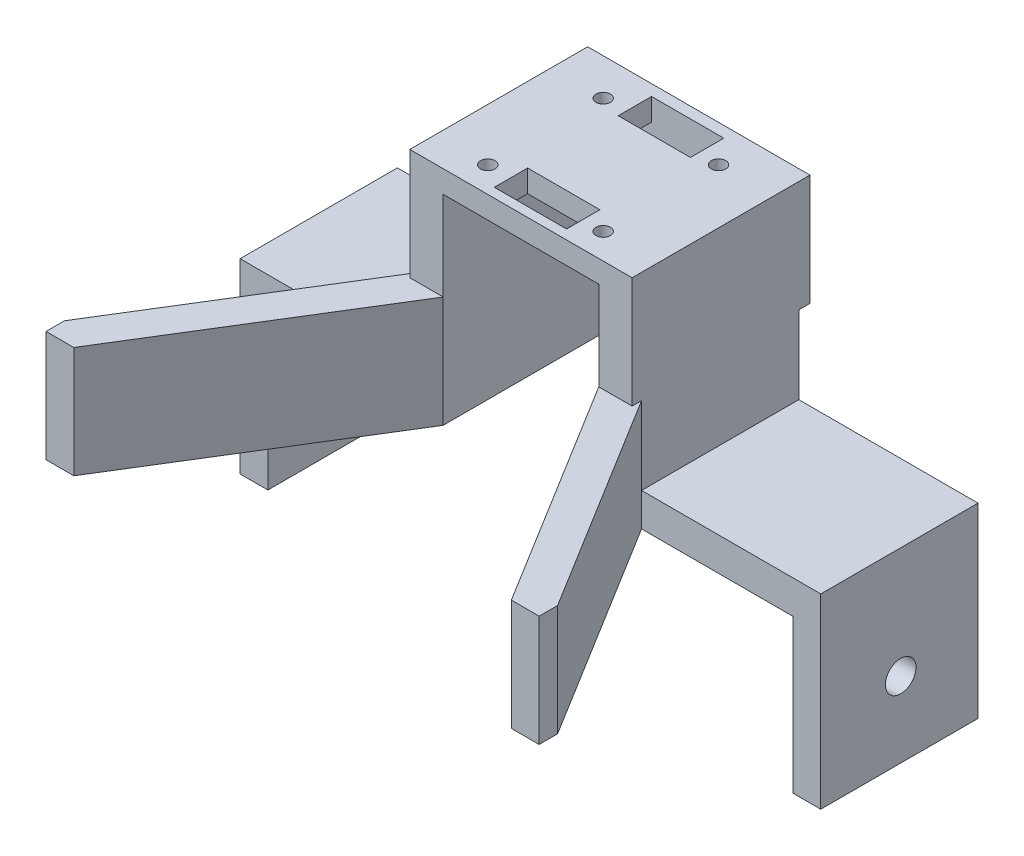
SolidWorks part; units mm, degrees
ref_plane "Front Plane" through (0, 0, 0) normal (0, 0, 1) x (1, 0, 0)
ref_plane "Top Plane" through (0, 0, 0) normal (0, 1, 0) x (1, 0, 0)
ref_plane "Right Plane" through (0, 0, 0) normal (1, 0, 0) x (0, 0, -1)
sketch "Sketch1" plane through (0, 0, 0) normal (0, 1, 0) x (1, 0, 0)
  line L0 (6.35, 4.2199) -> (-24.6, 54.3595)
  line L2 (6.35, 0) -> (6.35, 4.2199)
  line L5 (0, 0) -> (-32.22, 52.1971)
  line L6 (-32.22, 52.1971) -> (-32.22, 90.2971)
  line L7 (-32.22, 90.2971) -> (-24.6, 90.2971)
  line L8 (-24.6, 90.2971) -> (-24.6, 54.3595)
  line L9 (0, 0) -> (6.35, 0)
  line L10 (-50, 107.5436) -> (-50, 5.6571) construction
  point P3 (0, 0)
  point P9 (0, 0)
  dimension "D1" = 17.78
  dimension "D2" = 50
  dimension "D3" = 7.62
  dimension "D4" = 6.35
  dimension "D5" = 4.2199
  dimension "D6" = 7.62
  dimension "D7" = 38.1
extrude "Boss-Extrude1" add sketch "Sketch1" along normal blind 25.4
sketch "Sketch7" plane through (-24.6, 0, 0) normal (1, 0, 0) x (0, 0, -1)
  line L0 (90.2971, 25.4) -> (90.2971, 0) construction
  line L1 (54.3595, 0) -> (90.2971, 0)
  line L2 (54.3595, 0) -> (54.3595, 7.62)
  line L3 (54.3595, 7.62) -> (90.2971, 7.62)
  line L4 (90.2971, 0) -> (90.2971, 7.62)
  dimension "D1" = 7.62
extrude "Boss-Extrude3" add sketch "Sketch7" along normal blind 40.95
sketch "Sketch8" plane through (0, 0, 0) normal (0, -1, 0) x (1, 0, 0)
  line L0 (16.35, -90.2971) -> (-32.22, -90.2971) construction
  line L1 (16.35, -54.3595) -> (10, -54.3595)
  line L2 (16.35, -54.3595) -> (16.35, -90.2971)
  line L3 (16.35, -90.2971) -> (10, -90.2971)
  line L4 (10, -54.3595) -> (10, -90.2971)
  dimension "D1" = 6.35
extrude "Boss-Extrude4" add sketch "Sketch8" along normal blind 35
ref_plane "Plane2" through (-50, 0, 0) normal (-1, 0, 0) x (0, 0, 1)
mirror "Mirror6" about plane through (-50, 0, 0) normal (-1, 0, 0) of bodies 105 103
sketch "Sketch9" plane through (0, 25.4, 0) normal (0, 1, 0) x (1, 0, 0)
  line L1 (-67.78, 90.2971) -> (-75.4, 90.2971)
  line L2 (-67.78, 90.2971) -> (-67.78, 54.3595)
  line L3 (-67.78, 54.3595) -> (-75.4, 54.3595)
  line L4 (-75.4, 90.2971) -> (-75.4, 54.3595)
  line L5 (-32.22, 90.2971) -> (-24.6, 90.2971)
  line L6 (-32.22, 90.2971) -> (-32.22, 54.3595)
  line L7 (-32.22, 54.3595) -> (-24.6, 54.3595)
  line L8 (-24.6, 90.2971) -> (-24.6, 54.3595)
extrude "Boss-Extrude5" add sketch "Sketch9" along normal blind 25.4
sketch "Sketch10" plane through (-67.78, 0, 0) normal (1, 0, 0) x (0, 0, -1)
  line L0 (90.2971, 50.8) -> (90.2971, 7.62) construction
  line L1 (54.3595, 50.8) -> (90.2971, 50.8)
  line L2 (54.3595, 50.8) -> (54.3595, 45.72)
  line L3 (54.3595, 45.72) -> (90.2971, 45.72)
  line L4 (90.2971, 50.8) -> (90.2971, 45.72)
  dimension "D1" = 5.08
extrude "Boss-Extrude6" add sketch "Sketch10" along normal up to next
sketch "Sketch11" plane through (0, 50.8, 0) normal (0, 1, 0) x (1, 0, 0)
  line L0 (-75.4, 54.3595) -> (-24.6, 54.3595) construction
  line L1 (-58.255, 54.3595) -> (-41.745, 54.3595)
  line L2 (-58.255, 54.3595) -> (-58.255, 61.9795)
  line L3 (-58.255, 61.9795) -> (-41.745, 61.9795)
  line L4 (-41.745, 54.3595) -> (-41.745, 61.9795)
  line L5 (-24.6, 90.2971) -> (-75.4, 90.2971) construction
  line L6 (-58.255, 90.2971) -> (-41.745, 90.2971)
  line L7 (-58.255, 90.2971) -> (-58.255, 82.6771)
  line L8 (-58.255, 82.6771) -> (-41.745, 82.6771)
  line L9 (-41.745, 90.2971) -> (-41.745, 82.6771)
  line L10 (-24.6, 54.3595) -> (-24.6, 90.2971) construction
  dimension "D1" = 16.51
  dimension "D2" = 17.145
  dimension "D3" = 17.145
  dimension "D6" = 7.62
extrude "Cut-Extrude1" cut sketch "Sketch11" against normal up to next
sketch "Sketch12" plane through (0, 0, -54.3595) normal (0, 0, 1) x (1, 0, 0)
  line L0 (-75.4, 50.8) -> (-24.6, 50.8)
  line L1 (-24.6, 50.8) -> (-24.6, 25.4)
  line L2 (-24.6, 25.4) -> (-32.22, 25.4)
  line L3 (-32.22, 25.4) -> (-32.22, 45.72)
  line L4 (-32.22, 45.72) -> (-67.78, 45.72)
  line L5 (-67.78, 45.72) -> (-67.78, 25.4)
  line L6 (-67.78, 25.4) -> (-75.4, 25.4)
  line L7 (-75.4, 25.4) -> (-75.4, 50.8)
extrude "Boss-Extrude7" add sketch "Sketch12" along normal up to vertex (2.1624 mm away) up to point (-67.78, 25.4, -52.1971)
sketch "Sketch14" plane through (0, 0, -90.2971) normal (0, 0, -1) x (-1, 0, 0)
  line L0 (24.6, 50.8) -> (75.4, 50.8)
  line L1 (75.4, 50.8) -> (75.4, 25.4)
  line L2 (75.4, 50.8) -> (75.4, 7.62) construction
  line L3 (75.4, 25.4) -> (24.6, 25.4)
  line L4 (24.6, 50.8) -> (24.6, 7.62) construction
  line L5 (24.6, 25.4) -> (24.6, 50.8)
extrude "Boss-Extrude9" add sketch "Sketch14" along normal blind 2.54
sketch "Sketch16" plane through (16.35, 0, 0) normal (1, 0, 0) x (0, 0, -1)
  line L0 (54.3595, 0) -> (90.2971, 0) construction
  line L1 (90.2971, 7.62) -> (90.2971, -35) construction
  point P0 (72.634, -17.78)
  dimension "D1" = 17.78
  dimension "D2" = 17.6632
hole_wizard "M6 Clearance Hole2" positions "Sketch16" profile "Sketch17" hole size "M6" standard "ANSI Metric" end condition through all
sketch "Sketch17" plane through (16.35, -17.78, -72.634) normal (0, 1, 0) x (0, 0, -1)
  line L0 (0, 0) -> (0, 132.7)
  line L1 (0, 132.7) -> (3.5, 132.7)
  line L2 (3.5, 132.7) -> (3.5, 0)
  line L5 (3.5, 0) -> (0, 0)
  line L11 (0, -6.35) -> (0, 107.95) construction
  dimension "Thru Hole Dia." = 7
  dimension "Thru Hole Depth" = 132.7
sketch "Sketch18" plane through (0, 45.72, 0) normal (0, -1, 0) x (-1, 0, 0)
  line L0 (67.78, 52.1971) -> (32.22, 52.1971) construction
  circle A0 centre (37.0802, 58.0645) radius 1.651
  circle A1 centre (63.4454, 58.0645) radius 1.651
  circle A2 centre (63.4454, 84.4297) radius 1.651
  circle A3 centre (37.0802, 84.4297) radius 1.651
  dimension "D1" = 3.302
  dimension "D4" = 5.8674
  dimension "D2" = 2
  dimension "D3" = 2
extrude "Cut-Extrude2" cut sketch "Sketch18" against normal up to next
sketch "Sketch19" plane through (0, 45.72, 0) normal (0, -1, 0) x (1, 0, 0)
  line L0 (-32.22, -90.2971) -> (-67.78, -90.2971) construction
  line L1 (-42.126, -64.0729) -> (-34.506, -64.0729)
  line L2 (-42.126, -64.0729) -> (-42.126, -80.5829)
  line L3 (-42.126, -80.5829) -> (-34.506, -80.5829)
  line L4 (-34.506, -64.0729) -> (-34.506, -80.5829)
  line L5 (-32.22, -52.1971) -> (-32.22, -90.2971) construction
  line L8 (-58.255, -90.2971) -> (-67.78, -90.2971) construction
  line L9 (-57.874, -64.0729) -> (-65.494, -64.0729)
  line L10 (-57.874, -64.0729) -> (-57.874, -80.5829)
  line L11 (-57.874, -80.5829) -> (-65.494, -80.5829)
  line L12 (-65.494, -64.0729) -> (-65.494, -80.5829)
  line L13 (-67.78, -90.2971) -> (-67.78, -52.1971) construction
  dimension "D1" = 16.51
  dimension "D2" = 7.62
  dimension "D3" = 9.7142
  dimension "D4" = 2.286
  dimension "D5" = 9.7142
  dimension "D6" = 7.62
  dimension "D7" = 2.286
  dimension "D8" = 16.51
extrude "Cut-Extrude4" cut sketch "Sketch19" against normal blind 1.27
